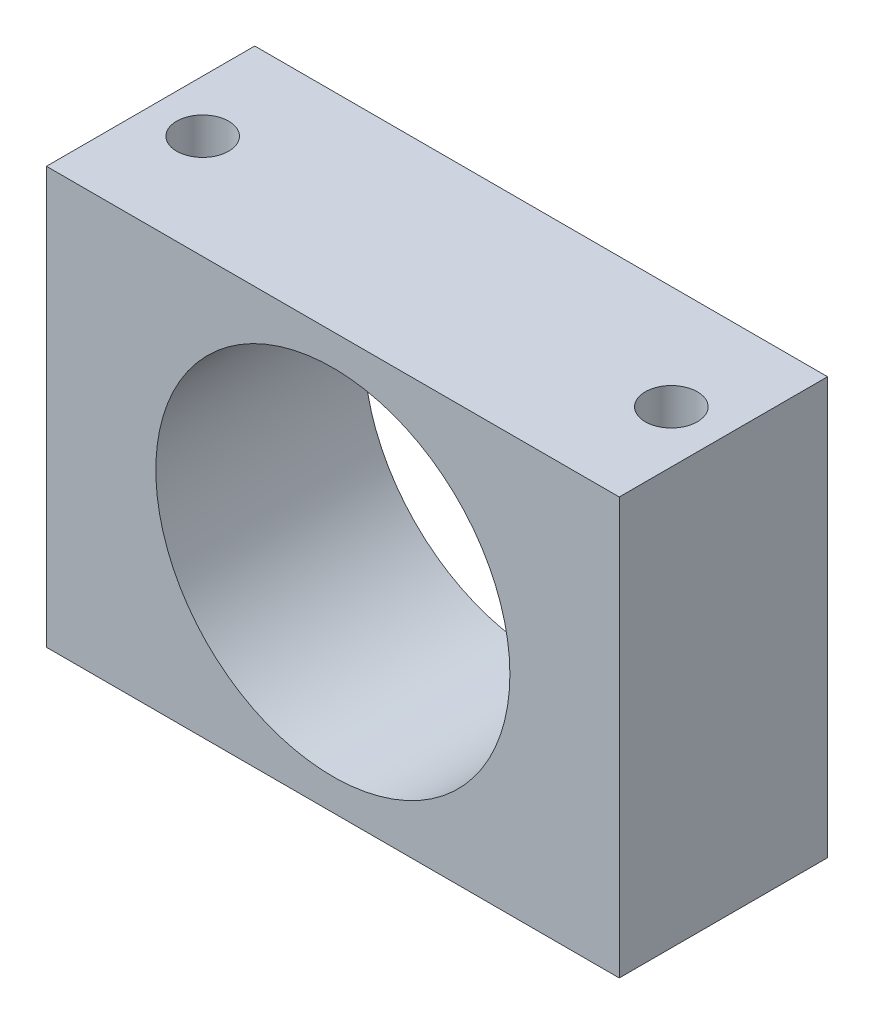
SolidWorks part; units mm, degrees
ref_plane "Plano frontal" through (0, 0, 0) normal (0, 0, 1) x (1, 0, 0)
ref_plane "Plano superior" through (0, 0, 0) normal (0, 1, 0) x (1, 0, 0)
ref_plane "Plano direito" through (0, 0, 0) normal (1, 0, 0) x (0, 0, -1)
sketch "Sketch1" plane through (0, 0, 0) normal (0, 0, 1) x (1, 0, 0)
  line L1 (-27.5, 20) -> (27.5, 20)
  line L2 (-27.5, 20) -> (-27.5, -20)
  line L3 (-27.5, -20) -> (27.5, -20)
  line L4 (27.5, 20) -> (27.5, -20)
  line L5 (0, -20) -> (0, 20) construction
  line L6 (-27.5, 0) -> (27.5, 0) construction
  circle A0 centre (0, 0) radius 17
  point P0 (0, 0)
  dimension "D3" = 34
  dimension "D1" = 55
  dimension "D2" = 40
extrude "Boss-Extrude1" add sketch "Sketch1" along normal blind 20
hole_wizard "M6 Tapped Hole1" positions "Sketch4" profile "Sketch6" tap size "M6" standard "ISO"
sketch "Sketch4" plane through (0, 20, 0) normal (0, 1, 0) x (1, 0, 0)
  line L5 (0, 20) -> (0, -20) construction
  line L7 (27.5, -20) -> (-27.5, -20) construction
  line L11 (-22.5, -10) -> (22.5, -10) construction
  point P148 (22.5, -10)
  point P183 (-22.5, -10)
  dimension "D1" = 45
sketch "Sketch6" plane through (-22.5, 20, 10) normal (1, 0, 0) x (0, 0, 1)
  line L0 (0, 0) -> (0, 18.5022)
  line L1 (0, 18.5022) -> (2.5, 17)
  line L2 (2.5, 17) -> (2.5, 0)
  line L5 (2.5, 0) -> (0, 0)
  line L10 (0, 18.5022) -> (-2.5, 17) construction
  line L11 (0, -6.35) -> (0, 107.95) construction
  dimension "Tap Drill Dia." = 5
  dimension "Tap Drill Depth" = 17
  dimension "Drill Angle" = 118
cosmetic thread "Hole Thread4"
cosmetic thread "Hole Thread5"
hole_wizard "M4x0.7 Tapped Hole3" positions "Sketch11" profile "Sketch12" tap size "M4x0.7" standard "JIS"
sketch "Sketch11" plane through (-5.2895, -11.1301, 0) normal (0, 0, -1) x (-1, 0, 0)
  point P0 (-24.342, 0.1301)
  point P1 (-24.342, 22.1301)
  point P2 (-5.2895, 33.1301)
  point P3 (13.7631, 22.1301)
sketch "Sketch12" plane through (19.0526, -11, 0) normal (1, 0, 0) x (0, 1, 0)
  line L0 (0, 0) -> (0, 12.9914)
  line L1 (0, 12.9914) -> (1.65, 12)
  line L2 (1.65, 12) -> (1.65, 0)
  line L3 (1.65, 0) -> (0, 0)
  line L4 (0, 12.9914) -> (-1.65, 12) construction
  line L5 (0, -6.35) -> (0, 107.95) construction
  dimension "Tap Drill Dia." = 3.3
  dimension "Tap Drill Depth" = 12
  dimension "Drill Angle" = 118
